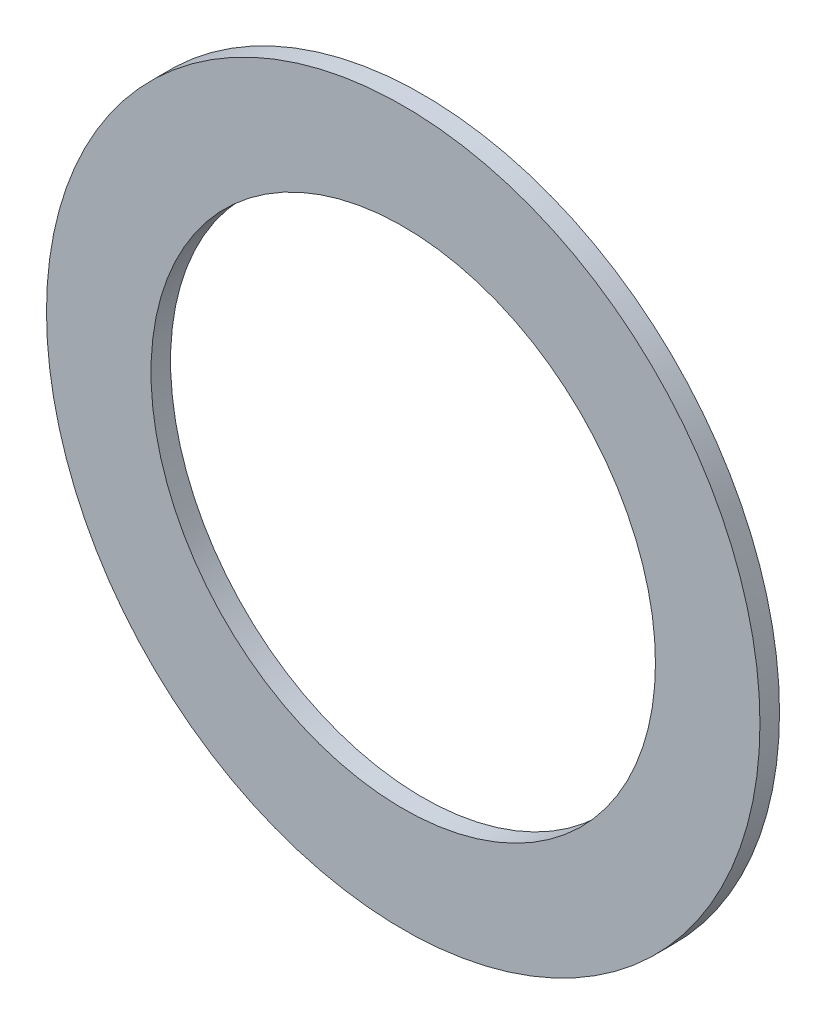
SolidWorks part; units mm, degrees
ref_plane "Front Plane" through (0, 0, 0) normal (0, 0, 1) x (1, 0, 0)
ref_plane "Top Plane" through (0, 0, 0) normal (0, 1, 0) x (1, 0, 0)
ref_plane "Right Plane" through (0, 0, 0) normal (1, 0, 0) x (0, 0, -1)
sketch "Sketch1" plane through (0, 0, 0) normal (0, 0, 1) x (1, 0, 0)
  circle A0 centre (0, 0) radius 73
  circle A1 centre (0, 0) radius 51.6125
  dimension "D1" = 146
  dimension "D2" = 103.225
extrude "Boss-Extrude1" add sketch "Sketch1" along normal blind 4 contours A0 A1
